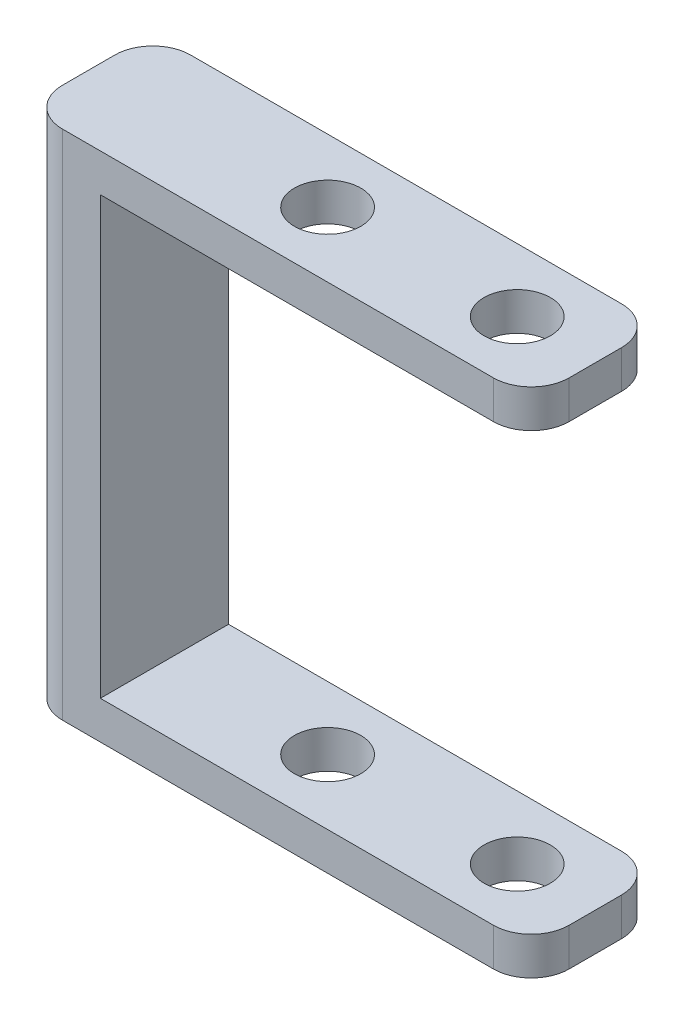
SolidWorks part; units mm, degrees
ref_plane "前视基准面" through (0, 0, 0) normal (0, 0, 1) x (1, 0, 0)
ref_plane "上视基准面" through (0, 0, 0) normal (0, 1, 0) x (1, 0, 0)
ref_plane "右视基准面" through (0, 0, 0) normal (1, 0, 0) x (0, 0, -1)
other "Configuration Table"
sketch "草图1" plane through (0, 0, 0) normal (0, 1, 0) x (1, 0, 0)
  line L1 (-14.007, 3.6484) -> (8.7185, 3.6484)
  line L2 (-16.007, 1.6484) -> (-16.007, -1.1125)
  line L3 (-14.007, -3.1125) -> (8.7185, -3.1125)
  line L4 (10.7185, 1.6484) -> (10.7185, -1.1125)
  circle A0 centre (-3.4452, 0.3092) radius 1.75
  circle A1 centre (6.5548, 0.3092) radius 1.75
  arc A2 (8.7185, -3.1125) -> (10.7185, -1.1125) centre (8.7185, -1.1125) ccw
  arc A3 (8.7185, 3.6484) -> (10.7185, 1.6484) centre (8.7185, 1.6484) cw
  arc A4 (-16.007, -1.1125) -> (-14.007, -3.1125) centre (-14.007, -1.1125) ccw
  arc A5 (-14.007, 3.6484) -> (-16.007, 1.6484) centre (-14.007, 1.6484) ccw
  dimension "D1" = 3.5
  dimension "D2" = 3.5
  dimension "D4" = 2
  dimension "D3" = 10
extrude "凸台-拉伸1" add sketch "草图1" along normal blind 27
sketch "草图2" plane through (0, 0, 3.1125) normal (0, 0, 1) x (1, 0, 0)
  line L0 (-14.007, 27) -> (8.7185, 27) construction
  line L1 (-12.007, 25) -> (17.0451, 25)
  line L2 (-12.007, 25) -> (-12.007, 2)
  line L3 (-12.007, 2) -> (17.0451, 2)
  line L4 (17.0451, 25) -> (17.0451, 2)
  line L5 (-14.007, 0) -> (8.7185, 0) construction
  line L6 (-16.007, 27) -> (-16.007, 0) construction
  dimension "D1" = 2
  dimension "D2" = 2
  dimension "D3" = 4
extrude "切除-拉伸1" cut sketch "草图2" against normal through all both
